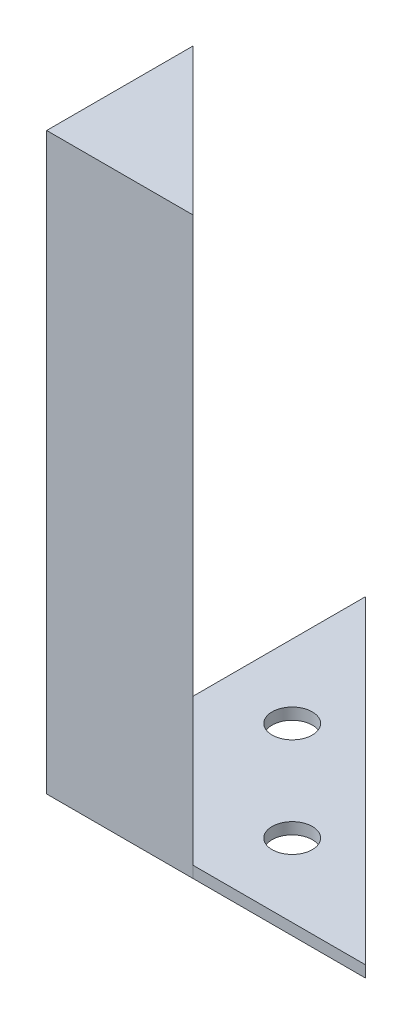
SolidWorks part; units mm, degrees
ref_plane "前视基准面" through (0, 0, 0) normal (0, 0, 1) x (1, 0, 0)
ref_plane "上视基准面" through (0, 0, 0) normal (0, 1, 0) x (1, 0, 0)
ref_plane "右视基准面" through (0, 0, 0) normal (1, 0, 0) x (0, 0, -1)
sketch "草图1" plane through (0, 0, 0) normal (0, 1, 0) x (1, 0, 0)
  line L0 (0, 0) -> (12.7279, 0)
  line L5 (0, 0) -> (0, 12.7279)
  line L6 (0, 12.7279) -> (12.7279, 0)
  dimension "D1" = 18
extrude "凸台-拉伸1" add sketch "草图1" along normal blind 50
sketch "草图2" plane through (0, 0, 0) normal (0, -1, 0) x (-1, 0, 0)
  line L0 (-6.364, 6.364) -> (-50006.364, 6.364) construction
  line L1 (-12.7279, 0) -> (0, 12.7279) construction
  line L2 (-6.364, 6.364) -> (-6.364, 50006.364) construction
  line L3 (0, 12.7279) -> (0, 27.7279)
  line L4 (0, 27.7279) -> (-27.7279, 0)
  line L5 (-27.7279, 0) -> (-12.7279, 0)
  line L6 (-12.7279, 0) -> (0, 12.7279)
  point P4 (-6.364, 6.364)
  dimension "D1" = 15
extrude "凸台-拉伸2" add sketch "草图2" against normal blind 1 separate body
sketch "草图3" plane through (0, 0, 0) normal (0, -1, 0) x (-1, 0, 0)
  line L0 (-6.364, 6.364) -> (-50006.364, 6.364) construction
  line L1 (-12.7279, 0) -> (0, 12.7279) construction
  line L2 (-6.364, 6.364) -> (-6.364, 50006.364) construction
  line L4 (0, 0) -> (-12.7279, 0) construction
  line L5 (0, 12.7279) -> (0, 0) construction
  circle A0 centre (-15, 6.364) radius 1.75
  circle A1 centre (-6.364, 15) radius 1.75
  point P8 (-6.364, 6.364)
  point P11 (-6.364, 12.0358)
  point P12 (-11.7733, 6.364)
  dimension "D3" = 3.5
  dimension "D1" = 15
  dimension "D2" = 15
extrude "切除-拉伸1" cut sketch "草图3" against normal blind 1
shell "抽壳1" thickness 2
sketch "草图4" plane through (6.364, 0, -6.364) normal (0.7071, 0, -0.7071) x (-0.7071, 0, -0.7071)
  line L0 (0, 48) -> (0, 0) construction
  line L1 (-9, 50) -> (9, 50) construction
  line L2 (-2.9968, 42) -> (3, 42) construction
  line L3 (-2.9968, 42.5) -> (3, 42.5)
  line L4 (-2.9968, 41.5) -> (3, 41.5)
  circle A0 centre (0, 42) radius 8 construction
  arc A1 (-2.9968, 42.5) -> (-2.9968, 41.5) centre (-2.9968, 42) ccw
  arc A2 (3, 41.5) -> (3, 42.5) centre (3, 42) ccw
  point P8 (0.0016, 42)
  dimension "D1" = 16
  dimension "D4" = 0.5
  dimension "D2" = 2.9968
  dimension "D3" = 3
extrude "切除-拉伸2" cut sketch "草图4" against normal blind 2
